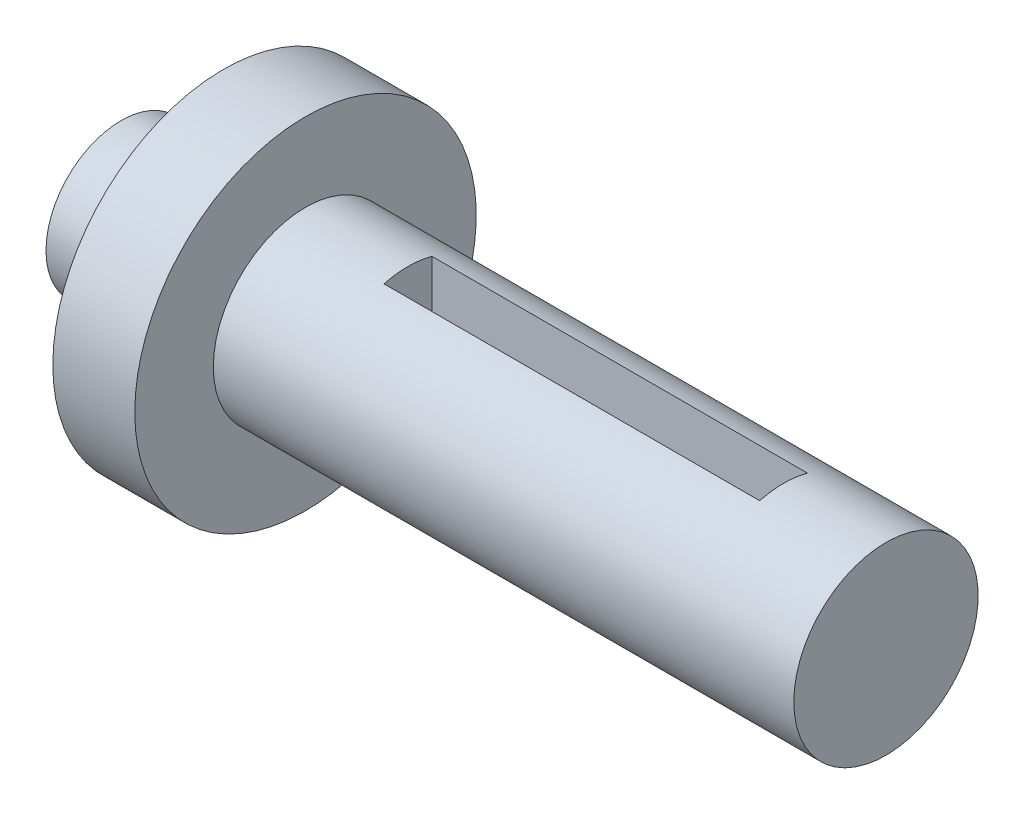
SolidWorks part; units mm, degrees
ref_plane "Front Plane" through (0, 0, 0) normal (0, 0, 1) x (1, 0, 0)
ref_plane "Top Plane" through (0, 0, 0) normal (0, 1, 0) x (1, 0, 0)
ref_plane "Right Plane" through (0, 0, 0) normal (1, 0, 0) x (0, 0, -1)
sketch "Sketch1" plane through (0, 0, 0) normal (0, 1, 0) x (1, 0, 0)
  line L0 (0, 0) -> (112, 0)
  line L1 (112, 0) -> (112, 13.5)
  line L2 (112, 13.5) -> (27, 13.5)
  line L3 (27, 13.5) -> (27, 25)
  line L4 (27, 25) -> (15, 25)
  line L5 (15, 25) -> (15, 11)
  line L6 (15, 11) -> (0, 11)
  line L7 (0, 11) -> (0, 0)
  dimension "D1" = 13.5
  dimension "D2" = 11.5
  dimension "D3" = 112
  dimension "D4" = 85
  dimension "D5" = 15
  dimension "D6" = 11
revolve "Revolve3" add sketch "Sketch1" angle 360 about L0
sketch "Sketch4" plane through (0, 0, 0) normal (0, 1, 0) x (1, 0, 0)
  line L0 (0, 0) -> (88.5053, 0) construction
  line L1 (27, -25) -> (27, 25) construction
  line L2 (97, -3.5) -> (42, -3.5)
  line L3 (97, -3.5) -> (97, 3.5)
  line L4 (97, 3.5) -> (42, 3.5)
  line L5 (42, -3.5) -> (42, 3.5)
  line L6 (97, -3.5) -> (42, 3.5) construction
  line L7 (97, 3.5) -> (42, -3.5) construction
  point P3 (69.5, 0)
  dimension "D1" = 7
  dimension "D2" = 55
  dimension "D3" = 15
extrude "Cut-Extrude1" cut sketch "Sketch4" against normal through all both and the other way through all
